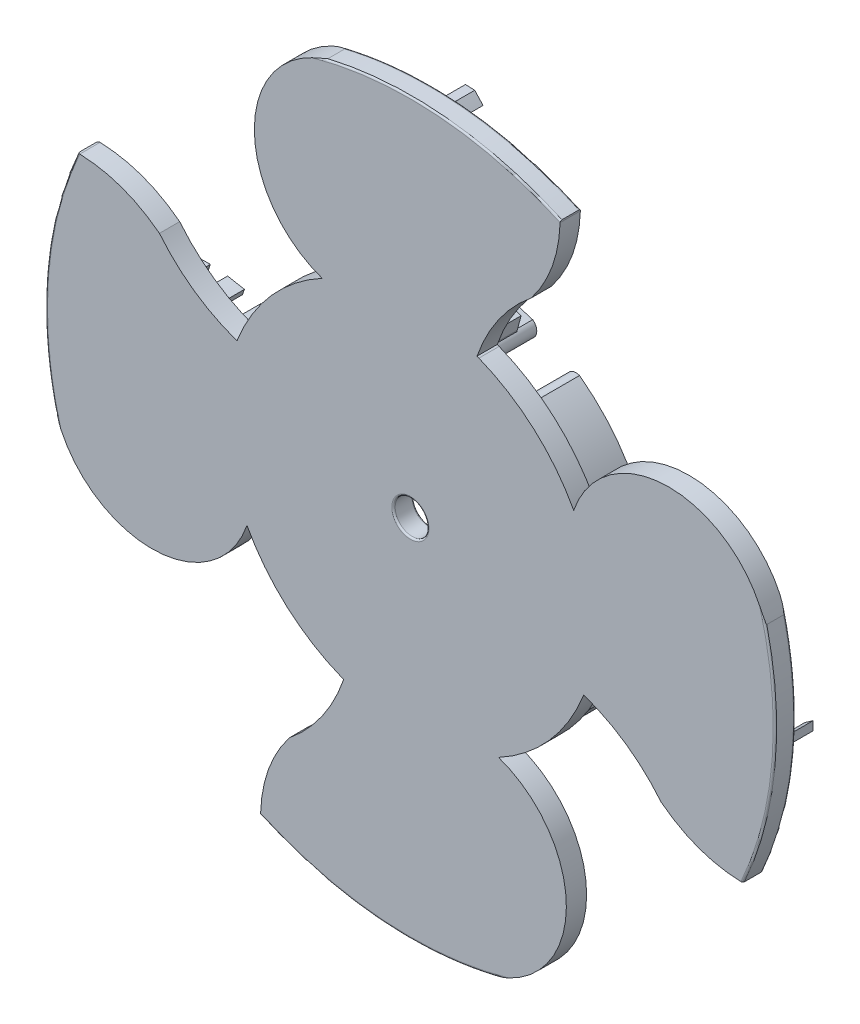
SolidWorks part; units mm, degrees
material "ABS PC"
ref_plane "Plan de face" through (0, 0, 0) normal (0, 0, 1) x (1, 0, 0)
ref_plane "Plan de dessus" through (0, 0, 0) normal (0, 1, 0) x (1, 0, 0)
ref_plane "Plan de droite" through (0, 0, 0) normal (1, 0, 0) x (0, 0, -1)
sketch "Esquisse1" plane through (0, 0, 0) normal (0, 0, 1) x (1, 0, 0)
  circle A0 centre (0, 0) radius 54
extrude "Boss.-Extru.1" add sketch "Esquisse1" along normal blind 3
sketch "Esquisse2" plane through (0, 0, 3) normal (0, 0, 1) x (1, 0, 0)
  circle A0 centre (0, 0) radius 2.5
extrude "Enlèv. mat.-Extru.1" cut sketch "Esquisse2" against normal through all
fillet "Congé1" radius 0.25 2 edges at (54, 0, 0) (54, 0, 3)
sketch "Esquisse4" plane through (0, 0, 3) normal (0, 0, 1) x (1, 0, 0)
  line L58 (10.1475, 25.5593) -> (9.8691, 25.6681)
  line L60 (38.9909, 44.188) -> (35.1121, 43.7399)
  line L61 (53.0261, 33.383) -> (38.9909, 44.188)
  line L62 (55.6552, 10.628) -> (53.0261, 33.383)
  line L63 (53.0261, 10.2093) -> (55.6552, 10.628)
  line L100 (35.1121, 43.7399) -> (22.2937, 50.024)
  line L101 (22.2937, 50.024) -> (22.1788, 48.9608)
  line L103 (10.2093, -53.0261) -> (10.628, -55.6552) [skipped]
  line L104 (10.628, -55.6552) -> (33.383, -53.0261) [skipped]
  line L105 (33.383, -53.0261) -> (44.188, -38.9909) [skipped]
  line L106 (44.188, -38.9909) -> (43.7399, -35.1121) [skipped]
  line L107 (25.5593, -10.1475) -> (25.6681, -9.8691) [skipped]
  line L108 (-53.0261, -10.2093) -> (-55.6552, -10.628) [skipped]
  line L109 (-55.6552, -10.628) -> (-53.0261, -33.383) [skipped]
  line L110 (-53.0261, -33.383) -> (-38.9909, -44.188) [skipped]
  line L111 (-38.9909, -44.188) -> (-35.1121, -43.7399) [skipped]
  line L112 (-10.1475, -25.5593) -> (-9.8691, -25.6681) [skipped]
  line L113 (-10.2093, 53.0261) -> (-10.628, 55.6552) [skipped]
  line L114 (-10.628, 55.6552) -> (-33.383, 53.0261) [skipped]
  line L115 (-33.383, 53.0261) -> (-44.188, 38.9909) [skipped]
  line L116 (-44.188, 38.9909) -> (-43.7399, 35.1121) [skipped]
  line L117 (-25.5593, 10.1475) -> (-25.6681, 9.8691) [skipped]
  line L131 (17.0613, -21.5676) -> (17.2947, -21.3809) [skipped]
  line L132 (-17.6715, -51.0266) -> (-18.6235, -53.5128) [skipped]
  line L133 (-18.6235, -53.5128) -> (2.3975, -62.6135) [skipped]
  line L134 (2.3975, -62.6135) -> (18.7725, -55.8612) [skipped]
  line L135 (18.7725, -55.8612) -> (20.3238, -52.278) [skipped]
  line L136 (20.3238, -52.278) -> (32.1752, -44.319) [skipped]
  line L137 (32.1752, -44.319) -> (31.3119, -43.6878) [skipped]
  line L138 (-35.3546, 40.8173) -> (-37.0317, 42.8848) [skipped]
  line L139 (-37.0317, 42.8848) -> (-55.4236, 29.2305) [skipped]
  line L140 (-55.4236, 29.2305) -> (-57.7634, 11.6731) [skipped]
  line L141 (-57.7634, 11.6731) -> (-55.4359, 8.5381) [skipped]
  line L142 (-55.4359, 8.5381) -> (-54.469, -5.7051) [skipped]
  line L143 (-54.469, -5.7051) -> (-53.4907, -5.273) [skipped]
  line L144 (-27.2088, -3.9917) -> (-27.1638, -4.2872) [skipped]
  line L145 (10.2093, -53.0261) -> (10.628, -55.6552)
  line L146 (10.628, -55.6552) -> (33.383, -53.0261)
  line L147 (33.383, -53.0261) -> (44.188, -38.9909)
  line L148 (44.188, -38.9909) -> (43.7399, -35.1121)
  line L149 (43.7399, -35.1121) -> (50.024, -22.2937)
  line L150 (50.024, -22.2937) -> (48.9608, -22.1788)
  line L151 (25.5593, -10.1475) -> (25.6681, -9.8691)
  line L152 (-53.0261, -10.2093) -> (-55.6552, -10.628)
  line L153 (-55.6552, -10.628) -> (-53.0261, -33.383)
  line L154 (-53.0261, -33.383) -> (-38.9909, -44.188)
  line L155 (-38.9909, -44.188) -> (-35.1121, -43.7399)
  line L156 (-35.1121, -43.7399) -> (-22.2937, -50.024)
  line L157 (-22.2937, -50.024) -> (-22.1788, -48.9608)
  line L158 (-10.1475, -25.5593) -> (-9.8691, -25.6681)
  line L159 (-10.2093, 53.0261) -> (-10.628, 55.6552)
  line L160 (-10.628, 55.6552) -> (-33.383, 53.0261)
  line L161 (-33.383, 53.0261) -> (-44.188, 38.9909)
  line L162 (-44.188, 38.9909) -> (-43.7399, 35.1121)
  line L163 (-43.7399, 35.1121) -> (-50.024, 22.2937)
  line L164 (-50.024, 22.2937) -> (-48.9608, 22.1788)
  line L165 (-25.5593, 10.1475) -> (-25.6681, 9.8691)
  arc A19 (53.0261, 10.2093) -> (24.1974, 13.0665) centre (38.273, 8.2201) ccw
  arc A27 (10.1475, 25.5593) -> (24.1974, 13.0665) centre (0, 0) cw
  arc A28 (17.9162, 37.1671) -> (9.8691, 25.6681) centre (33.9388, 17.3892) ccw
  circle A35 centre (0, 0) radius 53.75 construction
  arc A52 (25.5593, -10.1475) -> (13.0665, -24.1974) centre (0, 0) cw [skipped]
  arc A53 (10.2093, -53.0261) -> (13.0665, -24.1974) centre (8.2201, -38.273) ccw [skipped]
  arc A54 (37.1671, -17.9162) -> (25.6681, -9.8691) centre (17.3892, -33.9388) ccw [skipped]
  arc A55 (-10.1475, -25.5593) -> (-24.1974, -13.0665) centre (0, 0) cw [skipped]
  arc A56 (-53.0261, -10.2093) -> (-24.1974, -13.0665) centre (-38.273, -8.2201) ccw [skipped]
  arc A57 (-17.9162, -37.1671) -> (-9.8691, -25.6681) centre (-33.9388, -17.3892) ccw [skipped]
  arc A58 (-25.5593, 10.1475) -> (-13.0665, 24.1974) centre (0, 0) cw [skipped]
  arc A59 (-10.2093, 53.0261) -> (-13.0665, 24.1974) centre (-8.2201, 38.273) ccw [skipped]
  arc A60 (-37.1671, 17.9162) -> (-25.6681, 9.8691) centre (-17.3892, 33.9388) ccw [skipped]
  arc A67 (23.2296, -34.0994) -> (17.2947, -21.3809) centre (-1.9099, -38.0864) ccw [skipped]
  arc A68 (17.0613, -21.5676) -> (-0.7828, -27.4889) centre (0, 0) cw [skipped]
  arc A69 (-17.6715, -51.0266) -> (-0.7828, -27.4889) centre (-12.0177, -37.2555) ccw [skipped]
  arc A70 (-27.2088, -3.9917) -> (-23.4147, 14.4223) centre (0, 0) cw [skipped]
  arc A71 (-35.3546, 40.8173) -> (-23.4147, 14.4223) centre (-26.2553, 29.0354) ccw [skipped]
  arc A72 (-41.1458, -3.0677) -> (-27.1638, -4.2872) centre (-32.0289, 20.6972) ccw [skipped]
  arc A73 (25.5593, -10.1475) -> (13.0665, -24.1974) centre (0, 0) cw
  arc A74 (10.2093, -53.0261) -> (13.0665, -24.1974) centre (8.2201, -38.273) ccw
  arc A75 (37.1671, -17.9162) -> (25.6681, -9.8691) centre (17.3892, -33.9388) ccw
  arc A76 (-10.1475, -25.5593) -> (-24.1974, -13.0665) centre (0, 0) cw
  arc A77 (-53.0261, -10.2093) -> (-24.1974, -13.0665) centre (-38.273, -8.2201) ccw
  arc A78 (-17.9162, -37.1671) -> (-9.8691, -25.6681) centre (-33.9388, -17.3892) ccw
  arc A79 (-25.5593, 10.1475) -> (-13.0665, 24.1974) centre (0, 0) cw
  arc A80 (-10.2093, 53.0261) -> (-13.0665, 24.1974) centre (-8.2201, 38.273) ccw
  arc A81 (-37.1671, 17.9162) -> (-25.6681, 9.8691) centre (-17.3892, 33.9388) ccw
  spline S0 degree 2 poles (17.9162, 37.1671) (21.9727, 42.4265) (22.1788, 48.9608) knots 0 0 0 1 1 1
  spline S1 degree 2 poles (37.1671, -17.9162) (42.4265, -21.9727) (48.9608, -22.1788) knots 0 0 0 1 1 1
  spline S2 degree 2 poles (-17.9162, -37.1671) (-21.9727, -42.4265) (-22.1788, -48.9608) knots 0 0 0 1 1 1
  spline S3 degree 2 poles (-37.1671, 17.9162) (-42.4265, 21.9727) (-48.9608, 22.1788) knots 0 0 0 1 1 1
  point P42 (0, 0)
  point P45 (0, 0)
  point P47 (0, 0)
  point P50 (0, 0)
  point P51 (0, 0)
  point P59 (0, 0)
  point P68 (0, 0)
  point P69 (0, 0)
  dimension "D1" = 4
  dimension "D2" = 3
  dimension "D3" = 4
extrude "Enlèv. mat.-Extru.3" cut sketch "Esquisse4" against normal blind 6
sketch "Esquisse5" plane through (0, 0, 0) normal (0, 0, -1) x (-1, 0, 0)
  arc A0 (-19.5786, -14.4758) -> (8.3287, -22.8801) centre (0, 0) ccw
  arc A1 (-21.7832, -16.0591) -> (9.1206, -25.4797) centre (0, 0) ccw
  arc A2 (-21.7832, -16.0591) -> (-19.5786, -14.4758) centre (-20.4964, -15.5244) cw
  arc A4 (9.1206, -25.4797) -> (8.3287, -22.8801) centre (8.294, -24.3111) ccw
  arc A5 (-14.4758, 19.5786) -> (-22.8801, -8.3287) centre (0, 0) ccw
  arc A6 (-25.4797, -9.1206) -> (-22.8801, -8.3287) centre (-24.3111, -8.294) ccw
  arc A7 (-16.0591, 21.7832) -> (-25.4797, -9.1206) centre (0, 0) ccw
  arc A8 (-16.0591, 21.7832) -> (-14.4758, 19.5786) centre (-15.5244, 20.4964) cw
  arc A9 (19.5786, 14.4758) -> (-8.3287, 22.8801) centre (0, 0) ccw
  arc A10 (-9.1206, 25.4797) -> (-8.3287, 22.8801) centre (-8.294, 24.3111) ccw
  arc A11 (21.7832, 16.0591) -> (-9.1206, 25.4797) centre (0, 0) ccw
  arc A12 (21.7832, 16.0591) -> (19.5786, 14.4758) centre (20.4964, 15.5244) cw
  arc A13 (14.4758, -19.5786) -> (22.8801, 8.3287) centre (0, 0) ccw
  arc A14 (25.4797, 9.1206) -> (22.8801, 8.3287) centre (24.3111, 8.294) ccw
  arc A15 (16.0591, -21.7832) -> (25.4797, 9.1206) centre (0, 0) ccw
  arc A16 (16.0591, -21.7832) -> (14.4758, -19.5786) centre (15.5244, -20.4964) cw
  point P29 (0, 0)
  dimension "D1" = 4
extrude "Boss.-Extru.2" add sketch "Esquisse5" along normal blind 6
sketch "Esquisse6" plane through (0, 0, 0) normal (0, 0, -1) x (-1, 0, 0)
  line L16 (0, 0) -> (4.1032, 69.6599) construction
  line L17 (-9.4348, 25.9184) -> (-8.9334, 26.0941)
  line L18 (-9.7722, 25.7621) -> (-9.4348, 25.9184)
  line L19 (-9.8263, 25.9647) -> (-9.7722, 25.7621)
  line L20 (-2.1658, 53.6719) -> (-3.5326, 53.6124)
  line L29 (53.6719, 2.1658) -> (53.6124, 3.5326)
  line L30 (25.9647, 9.8263) -> (25.7621, 9.7722)
  line L31 (25.7621, 9.7722) -> (25.9184, 9.4348)
  line L32 (25.9184, 9.4348) -> (26.0941, 8.9334)
  line L33 (2.1658, -53.6719) -> (3.5326, -53.6124)
  line L34 (9.8263, -25.9647) -> (9.7722, -25.7621)
  line L35 (9.7722, -25.7621) -> (9.4348, -25.9184)
  line L36 (9.4348, -25.9184) -> (8.9334, -26.0941)
  line L37 (-53.6719, -2.1658) -> (-53.6124, -3.5326)
  line L38 (-25.9647, -9.8263) -> (-25.7621, -9.7722)
  line L39 (-25.7621, -9.7722) -> (-25.9184, -9.4348)
  line L40 (-25.9184, -9.4348) -> (-26.0941, -8.9334)
  spline S0 degree 3 poles (26.0941, 8.9334) (27.2397, 9.183) (29.5727, 9.8447) (33.7226, 10.9934) (38.4963, 10.4959) (44.6081, 9.1705) (49.2434, 5.5144) (52.517, 2.9387) (53.6719, 2.1658) knots 0 0 0 0 0.116456 0.242283 0.424247 0.586994 0.857841 0.998561 0.998561 0.998561 0.998561
  spline S1 degree 3 poles (53.6124, 3.5326) (52.1861, 4.9226) (48.8727, 7.7211) (42.7791, 10.9759) (35.7266, 12.1509) (30.074, 10.9584) (26.9991, 10.1019) (25.9647, 9.8263) knots 0.001064 0.001064 0.001064 0.001064 0.200578 0.429164 0.682971 0.892586 1 1 1 1
  spline S2 degree 3 poles (8.9334, -26.0941) (9.183, -27.2397) (9.8447, -29.5727) (10.9934, -33.7226) (10.4959, -38.4963) (9.1705, -44.6081) (5.5144, -49.2434) (2.9387, -52.517) (2.1658, -53.6719) knots 0 0 0 0 0.116456 0.242283 0.424247 0.586994 0.857841 0.998561 0.998561 0.998561 0.998561
  spline S3 degree 3 poles (3.5326, -53.6124) (4.9226, -52.1861) (7.7211, -48.8727) (10.9759, -42.7791) (12.1509, -35.7266) (10.9584, -30.074) (10.1019, -26.9991) (9.8263, -25.9647) knots 0.001064 0.001064 0.001064 0.001064 0.200578 0.429164 0.682971 0.892586 1 1 1 1
  spline S4 degree 3 poles (-26.0941, -8.9334) (-27.2397, -9.183) (-29.5727, -9.8447) (-33.7226, -10.9934) (-38.4963, -10.4959) (-44.6081, -9.1705) (-49.2434, -5.5144) (-52.517, -2.9387) (-53.6719, -2.1658) knots 0 0 0 0 0.116456 0.242283 0.424247 0.586994 0.857841 0.998561 0.998561 0.998561 0.998561
  spline S5 degree 3 poles (-53.6124, -3.5326) (-52.1861, -4.9226) (-48.8727, -7.7211) (-42.7791, -10.9759) (-35.7266, -12.1509) (-30.074, -10.9584) (-26.9991, -10.1019) (-25.9647, -9.8263) knots 0.001064 0.001064 0.001064 0.001064 0.200578 0.429164 0.682971 0.892586 1 1 1 1
  spline S8 degree 3 poles (-3.5326, 53.6124) (-4.9226, 52.1861) (-7.7211, 48.8727) (-10.9759, 42.7791) (-12.1509, 35.7266) (-10.9584, 30.074) (-10.1019, 26.9991) (-9.8263, 25.9647) knots 0.001064 0.001064 0.001064 0.001064 0.200578 0.429164 0.682971 0.892586 1 1 1 1
  spline S9 degree 3 poles (-8.9334, 26.0941) (-9.183, 27.2397) (-9.8447, 29.5727) (-10.9934, 33.7226) (-10.4959, 38.4963) (-9.1705, 44.6081) (-5.5144, 49.2434) (-2.9387, 52.517) (-2.1658, 53.6719) knots 0 0 0 0 0.116456 0.242283 0.424247 0.586994 0.857841 0.998561 0.998561 0.998561 0.998561
  point P53 (0, 0)
  point P67 (0, 0)
  dimension "D1" = 4
extrude "Boss.-Extru.3" add sketch "Esquisse6" along normal blind 3
sketch "Esquisse7" plane through (0, 0, 0) normal (0, 0, -1) x (-1, 0, 0)
  circle A0 centre (0, 0) radius 30
  circle A1 centre (0, 0) radius 32.5
  dimension "D1" = 65
  dimension "D2" = 60
extrude "Enlèv. mat.-Extru.4" cut sketch "Esquisse7" along normal blind 3
sketch "Esquisse8" plane through (0, 0, 0) normal (0, 0, -1) x (-1, 0, 0)
  circle A0 centre (0, 0) radius 35
  circle A1 centre (0, 0) radius 37.5
extrude "Enlèv. mat.-Extru.5" cut sketch "Esquisse8" along normal blind 3
sketch "Esquisse9" plane through (0, 0, 0) normal (0, 0, -1) x (-1, 0, 0)
  circle A0 centre (0, 0) radius 40
  circle A1 centre (0, 0) radius 42.5
extrude "Enlèv. mat.-Extru.6" cut sketch "Esquisse9" along normal blind 3
sketch "Esquisse10" plane through (0, 0, 0) normal (0, 0, -1) x (-1, 0, 0)
  circle A0 centre (0, 0) radius 45
  circle A1 centre (0, 0) radius 47.5
extrude "Enlèv. mat.-Extru.7" cut sketch "Esquisse10" along normal blind 3
sketch "Esquisse11" plane through (0, 0, 0) normal (0, 0, -1) x (-1, 0, 0)
  circle A0 centre (0, 0) radius 50
  circle A1 centre (0, 0) radius 52.5
extrude "Enlèv. mat.-Extru.8" cut sketch "Esquisse11" along normal blind 3
fillet "Congé2" radius 0.25 1 edges at (2.5, 0, 3)
fillet "Congé4" radius 0.25 1 edges at (2.5, 0, 0)
